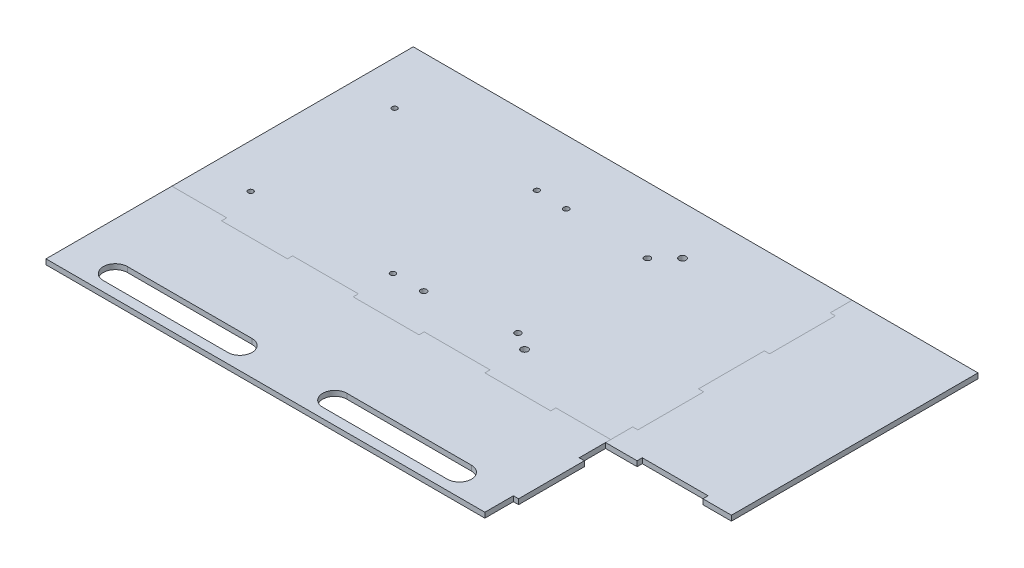
SolidWorks part; units mm, degrees
ref_plane "Front Plane" through (0, 0, 0) normal (0, 0, 1) x (1, 0, 0)
ref_plane "Top Plane" through (0, 0, 0) normal (0, 1, 0) x (1, 0, 0)
ref_plane "Right Plane" through (0, 0, 0) normal (1, 0, 0) x (0, 0, -1)
sketch "Sketch1" plane through (0, 0, 0) normal (0, 1, 0) x (1, 0, 0)
  line L0 (0, 0) -> (31.75, 0)
  line L1 (0, 0) -> (0, 139.7)
  line L2 (254, 0) -> (254, 12.7)
  line L3 (0, 139.7) -> (254, 139.7)
  line L4 (127, 0) -> (127, -33.6267) construction
  line L5 (107.95, 0) -> (107.95, -3)
  line L6 (107.95, -3) -> (146.05, -3)
  line L7 (146.05, -3) -> (146.05, 0)
  line L8 (222.25, -3) -> (222.25, 0)
  line L9 (184.15, -3) -> (222.25, -3)
  line L10 (184.15, 0) -> (184.15, -3)
  line L11 (69.85, 0) -> (69.85, -3)
  line L12 (69.85, -3) -> (31.75, -3)
  line L13 (31.75, -3) -> (31.75, 0)
  line L14 (69.85, 0) -> (107.95, 0)
  line L15 (146.05, 0) -> (184.15, 0)
  line L16 (222.25, 0) -> (254, 0)
  line L17 (254, 69.85) -> (265.2781, 69.85) construction
  line L18 (254, 127) -> (257, 127)
  line L19 (257, 127) -> (257, 88.9)
  line L20 (257, 88.9) -> (254, 88.9)
  line L21 (254, 12.7) -> (257, 12.7)
  line L22 (257, 50.8) -> (254, 50.8)
  line L23 (257, 12.7) -> (257, 50.8)
  line L24 (254, 127) -> (254, 139.7)
  line L25 (254, 50.8) -> (254, 88.9)
  dimension "D1" = 254
  dimension "D2" = 139.7
  dimension "D3" = 19.05
  dimension "D4" = 38.1
  dimension "D5" = 3
  dimension "D7" = 38.1
  dimension "D8" = 3
  dimension "D9" = 19.05
  dimension "D6" = 2
extrude "Boss-Extrude1" add sketch "Sketch1" along normal blind 3
sketch "Sketch2" plane through (0, 0, 0) normal (0, 1, 0) x (1, 0, 0)
  line L0 (0, 0) -> (31.75, 0)
  line L1 (0, 0) -> (0, -72.85)
  line L2 (254, 0) -> (254, -18.24)
  line L3 (0, -72.85) -> (254, -72.85)
  line L4 (0, 139.7) -> (0, 0) construction
  line L5 (107.95, 0) -> (107.95, -3)
  line L6 (107.95, -3) -> (146.05, -3)
  line L7 (146.05, -3) -> (146.05, 0)
  line L8 (127, 0) -> (127, -39.0108) construction
  line L9 (222.25, -3) -> (222.25, 0)
  line L10 (184.15, -3) -> (222.25, -3)
  line L11 (184.15, 0) -> (184.15, -3)
  line L12 (69.85, 0) -> (69.85, -3)
  line L13 (69.85, -3) -> (31.75, -3)
  line L14 (31.75, -3) -> (31.75, 0)
  line L15 (69.85, 0) -> (107.95, 0)
  line L16 (146.05, 0) -> (184.15, 0)
  line L17 (222.25, 0) -> (254, 0)
  line L18 (222.25, 0) -> (254, 0) construction
  line L19 (254, -36.425) -> (264.3748, -36.425) construction
  line L20 (254, -18.24) -> (257, -18.24)
  line L21 (257, -18.24) -> (257, -56.34)
  line L22 (257, -56.34) -> (254, -56.34)
  line L23 (254, -56.34) -> (254, -72.85)
  dimension "D1" = 254
  dimension "D2" = 72.85
  dimension "D3" = 19.05
  dimension "D4" = 38.1
  dimension "D5" = 3
  dimension "D7" = 0
  dimension "D8" = 38.1
  dimension "D9" = 3
  dimension "D10" = 16.51
  dimension "D6" = 2
extrude "Boss-Extrude2" add sketch "Sketch2" along normal blind 3 separate body
sketch "Sketch3" plane through (0, 0, 0) normal (0, 1, 0) x (1, 0, 0)
  line L0 (254, 139.7) -> (0, 139.7) construction
  line L1 (254, -3) -> (254, 12.7)
  line L2 (326.85, -3) -> (326.85, 139.7)
  line L3 (254, 139.7) -> (326.85, 139.7)
  line L4 (254, -3) -> (272.24, -3)
  line L5 (254, 127) -> (257, 127)
  line L6 (257, 127) -> (257, 88.9)
  line L7 (257, 88.9) -> (254, 88.9)
  line L8 (257, 50.8) -> (254, 50.8)
  line L9 (257, 12.7) -> (257, 50.8)
  line L10 (254, 12.7) -> (257, 12.7)
  line L11 (254, 127) -> (254, 139.7)
  line L12 (254, 50.8) -> (254, 88.9)
  line L13 (254, 0) -> (254, 12.7) construction
  line L14 (326.85, 68.35) -> (313.8041, 68.35) construction
  line L16 (254, 88.9) -> (257, 88.9) construction
  line L17 (257, 50.8) -> (254, 50.8) construction
  line L18 (272.24, -3) -> (272.24, 0)
  line L19 (272.24, 0) -> (310.34, 0)
  line L20 (310.34, 0) -> (310.34, -3)
  line L21 (310.34, -3) -> (326.85, -3)
  dimension "D1" = 142.7
  dimension "D2" = 72.85
  dimension "D3" = 3
  dimension "D4" = 38.1
  dimension "D5" = 0
  dimension "D6" = 0
  dimension "D7" = 0
  dimension "D8" = 0
  dimension "D9" = 38.1
  dimension "D10" = 16.51
  dimension "D11" = 3
  dimension "D12" = 38.1
extrude "Boss-Extrude3" add sketch "Sketch3" along normal blind 3 separate body
sketch "Sketch4" plane through (0, 3, 0) normal (0, 1, 0) x (1, 0, 0)
  line L0 (27.4554, -60.15) -> (99.5446, -60.15) construction
  line L1 (27.4554, -53.15) -> (99.5446, -53.15)
  line L2 (27.4554, -67.15) -> (99.5446, -67.15)
  line L3 (0, -72.85) -> (254, -72.85) construction
  line L4 (127, -72.85) -> (127, -72.1755) construction
  line L5 (226.5446, -60.15) -> (154.4554, -60.15) construction
  line L6 (226.5446, -53.15) -> (154.4554, -53.15)
  line L7 (226.5446, -67.15) -> (154.4554, -67.15)
  arc A0 (27.4554, -53.15) -> (27.4554, -67.15) centre (27.4554, -60.15) ccw
  arc A1 (99.5446, -67.15) -> (99.5446, -53.15) centre (99.5446, -60.15) ccw
  arc A2 (226.5446, -53.15) -> (226.5446, -67.15) centre (226.5446, -60.15) cw
  arc A3 (154.4554, -67.15) -> (154.4554, -53.15) centre (154.4554, -60.15) cw
  point P2 (63.5, -60.15)
  point P9 (127, -72.85)
  point P14 (190.5, -60.15)
  dimension "D2" = 7
  dimension "D1" = 12.7
  dimension "D3" = 63.5
extrude "Cut-Extrude1" cut sketch "Sketch4" against normal blind 3
sketch "Sketch5" plane through (0, 3, 0) normal (0, 1, 0) x (1, 0, 0)
  line L0 (0, 139.7) -> (0, 0) construction
  circle A0 centre (25.4, 20.2078) radius 1.5
  circle A1 centre (25.4, 103.5198) radius 1.5
  circle A2 centre (107.7, 20.2078) radius 1.5
  circle A3 centre (107.7, 103.5198) radius 1.5
  circle A4 centre (173.74, 101.4878) radius 1.75
  circle A5 centre (173.74, 26.5578) radius 1.75
  circle A6 centre (125.48, 20.2078) radius 1.75
  circle A7 centre (125.48, 102.7578) radius 1.5888
  circle A8 centre (183.9, 111.6478) radius 2
  circle A9 centre (183.9, 20.2078) radius 2
  dimension "D2" = 3
  dimension "D3" = 3
  dimension "D5" = 3
  dimension "D6" = 3
  dimension "D10" = 3.5
  dimension "D11" = 3.5
  dimension "D13" = 3.5
  dimension "D19" = 4
  dimension "D20" = 4
  dimension "D1" = 83.312
  dimension "D4" = 82.3
  dimension "D7" = 82.3
  dimension "D8" = 83.312
  dimension "D9" = 74.93
  dimension "D12" = 82.55
  dimension "D14" = 48.26
  dimension "D15" = 1.27
  dimension "D16" = 25.4
  dimension "D17" = 17.78
  dimension "D18" = 0
  dimension "D21" = 91.44
  dimension "D22" = 0
  dimension "D23" = 10.16
extrude "Cut-Extrude2" cut sketch "Sketch5" against normal blind 3
